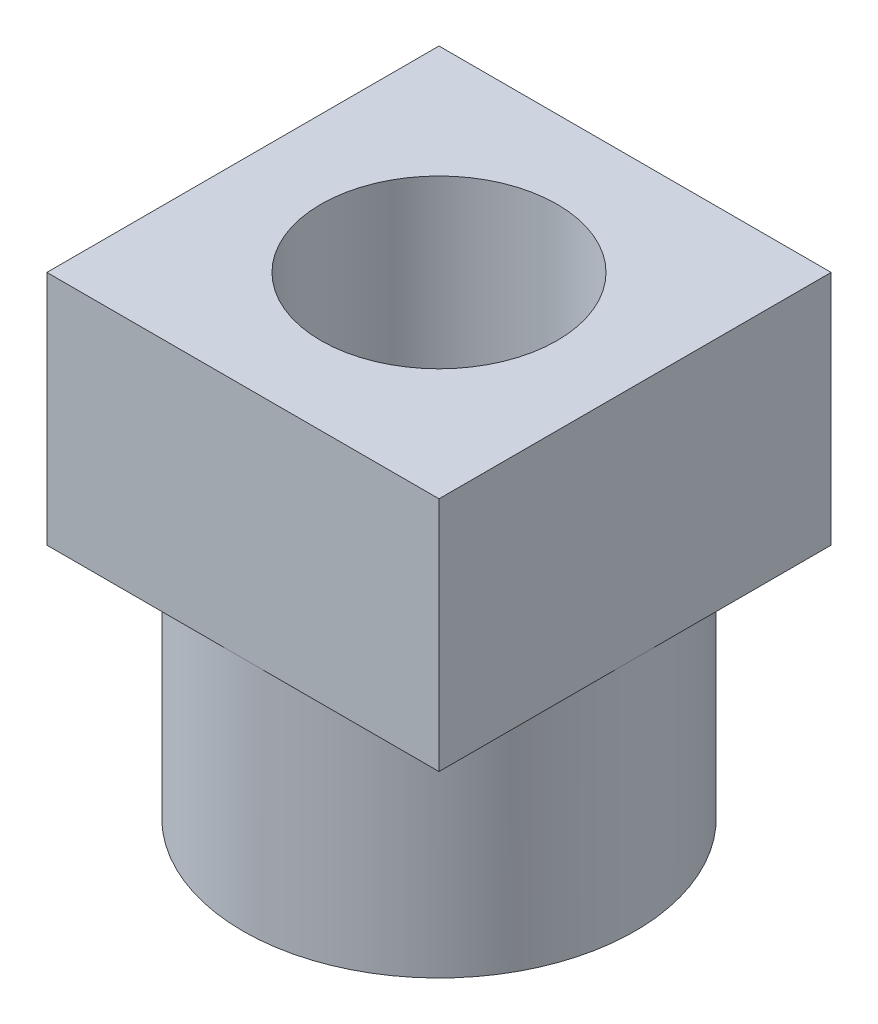
SolidWorks part; units mm, degrees
ref_plane "Front Plane" through (0, 0, 0) normal (0, 0, 1) x (1, 0, 0)
ref_plane "Top Plane" through (0, 0, 0) normal (0, 1, 0) x (1, 0, 0)
ref_plane "Right Plane" through (0, 0, 0) normal (1, 0, 0) x (0, 0, -1)
sketch "Sketch1" plane through (0, 0, 0) normal (0, 1, 0) x (1, 0, 0)
  line L1 (-8.3, -8.3) -> (8.3, -8.3)
  line L2 (-8.3, -8.3) -> (-8.3, 8.3)
  line L3 (-8.3, 8.3) -> (8.3, 8.3)
  line L4 (8.3, -8.3) -> (8.3, 8.3)
  circle A0 centre (0, 0) radius 5
  dimension "D5" = 10
  dimension "D1" = 16.6
  dimension "D2" = 16.6
  dimension "D3" = 8.3
  dimension "D4" = 8.3
extrude "Boss-Extrude1" add sketch "Sketch1" along normal blind 10 contours L2 L3 L4 L1
sketch "Sketch3" plane through (0, 0, 0) normal (0, -1, 0) x (1, 0, 0)
  circle A0 centre (0, 0) radius 5
  dimension "D1" = 10
extrude "Cut-Extrude1" cut sketch "Sketch3" against normal blind 10
sketch "Sketch4" plane through (0, 0, 0) normal (0, -1, 0) x (1, 0, 0)
  circle A0 centre (0, 0) radius 2.5
  circle A1 centre (0, 0) radius 8.3
  dimension "D1" = 5
extrude "Boss-Extrude2" add sketch "Sketch4" along normal blind 10
